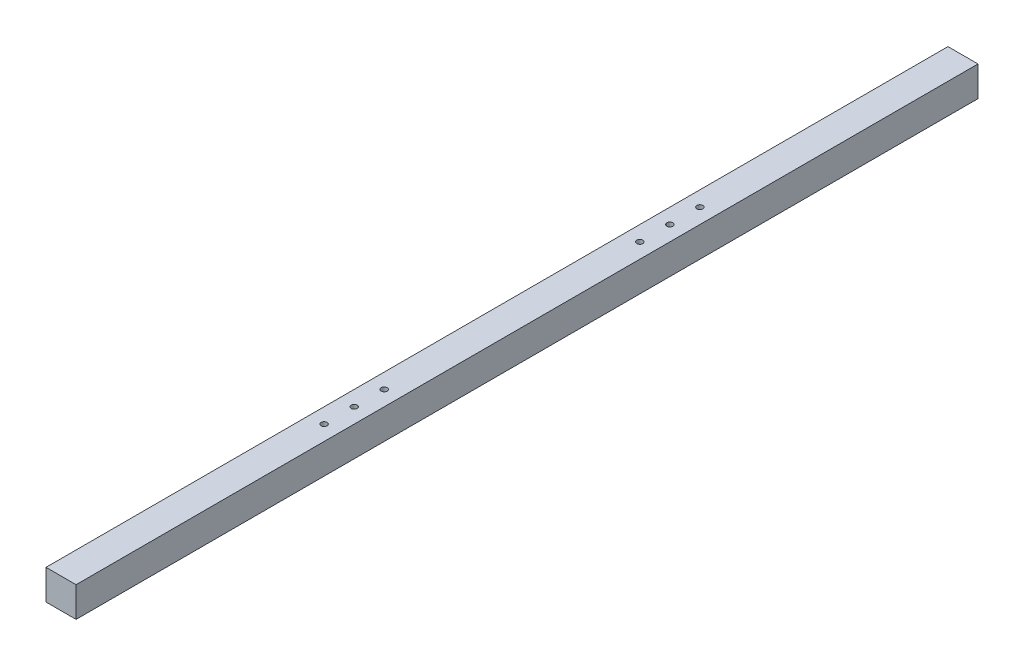
SolidWorks part; units mm, degrees
ref_plane "前视基准面" through (0, 0, 0) normal (0, 0, 1) x (1, 0, 0)
ref_plane "上视基准面" through (0, 0, 0) normal (0, 1, 0) x (1, 0, 0)
ref_plane "右视基准面" through (0, 0, 0) normal (1, 0, 0) x (0, 0, -1)
sketch "草图1" plane through (0, 0, 0) normal (0, 0, 1) x (1, 0, 0)
  line L1 (-10, 10) -> (10, 10)
  line L2 (-10, 10) -> (-10, -10)
  line L3 (-10, -10) -> (10, -10)
  line L4 (10, 10) -> (10, -10)
  line L5 (-10, 10) -> (10, -10) construction
  line L6 (-10, -10) -> (10, 10) construction
  line L11 (-8, 8) -> (8, -8) construction
  line L12 (-8, -8) -> (8, 8) construction
  point P0 (0, 0)
  point P6 (0, 0)
  dimension "D1" = 20
  dimension "D3" = 20
extrude "凸台-拉伸1" add sketch "草图1" along normal blind 600
sketch "草图2" plane through (0, 10, 0) normal (0, 1, 0) x (1, 0, 0)
  line L0 (0, 0) -> (0, -424.541) construction
  line L1 (10, 0) -> (-10, 0) construction
  line L2 (10, -300) -> (-10, -300) construction
  line L3 (10, -600) -> (10, 0) construction
  line L4 (-10, -600) -> (-10, 0) construction
  circle A0 centre (0, -195) radius 2
  circle A1 centre (0, -175) radius 2
  circle A2 centre (0, -215) radius 2
  circle A3 centre (0, -385) radius 2
  circle A4 centre (0, -405) radius 2
  circle A5 centre (0, -425) radius 2
  dimension "D1" = 4
  dimension "D2" = 195
  dimension "D3" = 20
  dimension "D4" = 20
extrude "切除-拉伸1" cut sketch "草图2" against normal through all both and the other way through all
